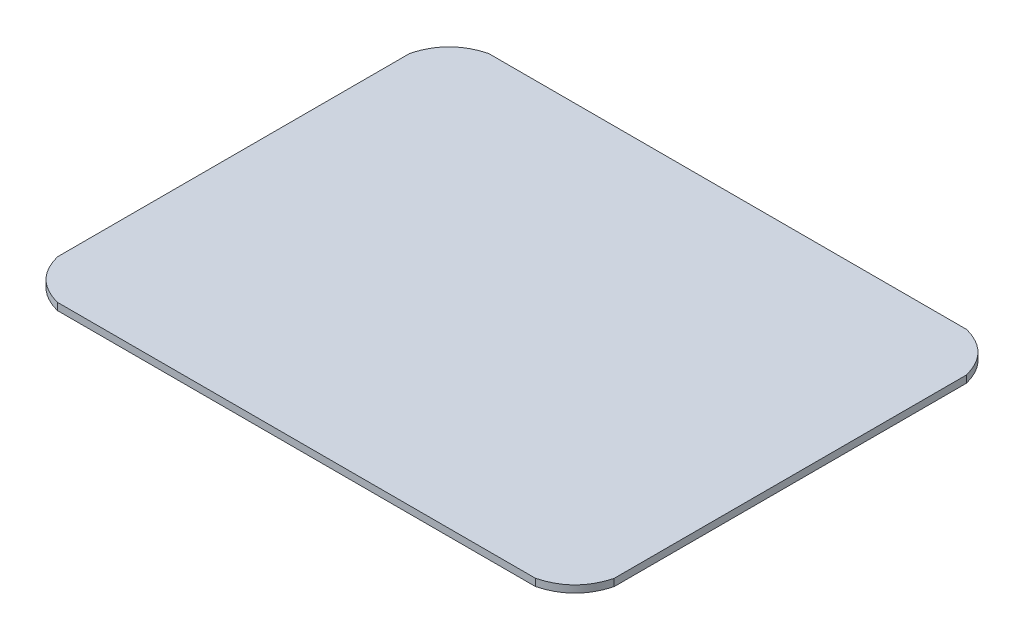
SolidWorks part; units mm, degrees
ref_plane "Front Plane" through (0, 0, 0) normal (0, 0, 1) x (1, 0, 0)
ref_plane "Top Plane" through (0, 0, 0) normal (0, 1, 0) x (1, 0, 0)
ref_plane "Right Plane" through (0, 0, 0) normal (1, 0, 0) x (0, 0, -1)
sketch "Sketch1" plane through (0, 0, 0) normal (0, 1, 0) x (1, 0, 0)
  line L12 (123.0312, -77.8605) -> (123.0312, 77.8605)
  line L13 (105.6239, 95.25) -> (-105.6239, 95.25)
  line L14 (-123.0312, 77.8605) -> (-123.0312, -77.8605)
  line L15 (-105.6239, -95.25) -> (105.6239, -95.25)
  spline S0 degree 2 poles (105.6239, -95.25) (119.3768, -91.6105) (123.0312, -77.8605) knots 0 0 0 1 1 1
  spline S1 degree 2 poles (-105.6239, -95.25) (-119.3768, -91.6105) (-123.0312, -77.8605) knots 0 0 0 1 1 1
  spline S2 degree 2 poles (-105.6239, 95.25) (-119.3768, 91.6105) (-123.0312, 77.8605) knots 0 0 0 1 1 1
  spline S3 degree 2 poles (105.6239, 95.25) (119.3768, 91.6105) (123.0312, 77.8605) knots 0 0 0 1 1 1
  point P0 (0, 0)
extrude "Boss-Extrude1" add sketch "Sketch1" along normal blind 3.175
